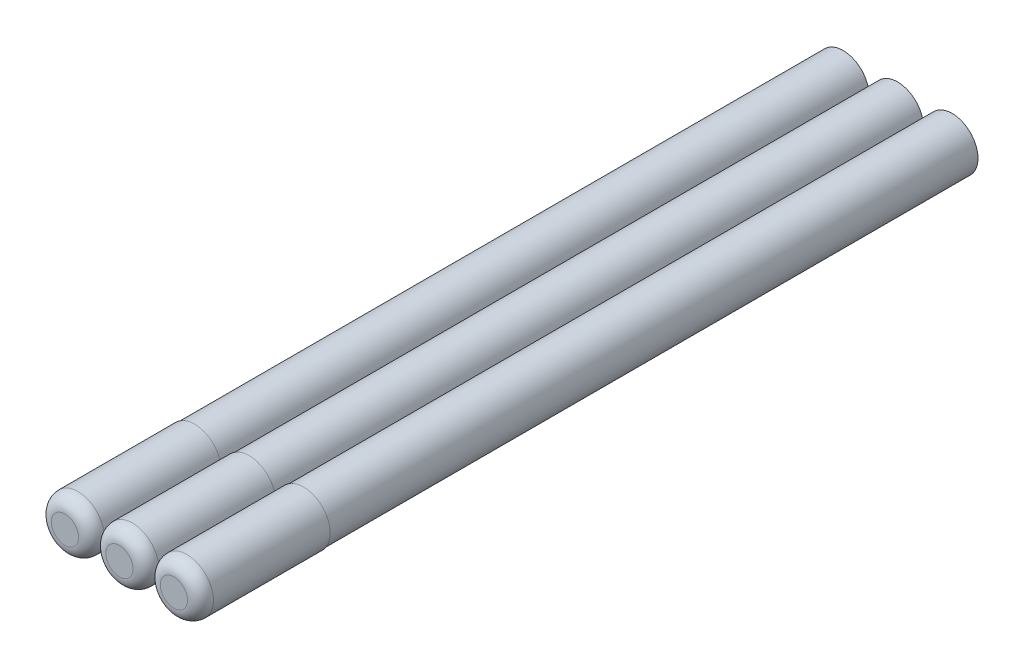
SolidWorks part; units mm, degrees
ref_plane "Спереди" through (0, 0, 0) normal (0, 0, 1) x (1, 0, 0)
ref_plane "Сверху" through (0, 0, 0) normal (0, 1, 0) x (1, 0, 0)
ref_plane "Справа" through (0, 0, 0) normal (1, 0, 0) x (0, 0, -1)
sketch "Эскиз1" plane through (0, 0, 0) normal (0, 0, 1) x (1, 0, 0)
  circle A0 centre (0, 0) radius 2
  circle A1 centre (4.2, 0) radius 2
  circle A2 centre (-4.2, 0) radius 2
  dimension "D1" = 4
  dimension "D2" = 4
  dimension "D3" = 4
  dimension "D4" = 4.2
  dimension "D5" = 4.2
extrude "Бобышка-Вытянуть1" add sketch "Эскиз1" along normal blind 50
sketch "Эскиз2" plane through (0, 0, 50) normal (0, 0, 1) x (1, 0, 0)
  circle A0 centre (0, 0) radius 2.05
  circle A1 centre (4.2, 0) radius 2.05
  circle A2 centre (-4.2, 0) radius 2.05
  dimension "D1" = 4.1
  dimension "D2" = 4.1
  dimension "D3" = 4.1
extrude "Бобышка-Вытянуть2" add sketch "Эскиз2" along normal blind 10 separate body
fillet "Скругление1" radius 1 1 edges at (-2.15, 0, 60)
fillet "Скругление2" radius 1 1 edges at (2.05, 0, 60)
fillet "Скругление3" radius 1 1 edges at (6.25, 0, 60)
